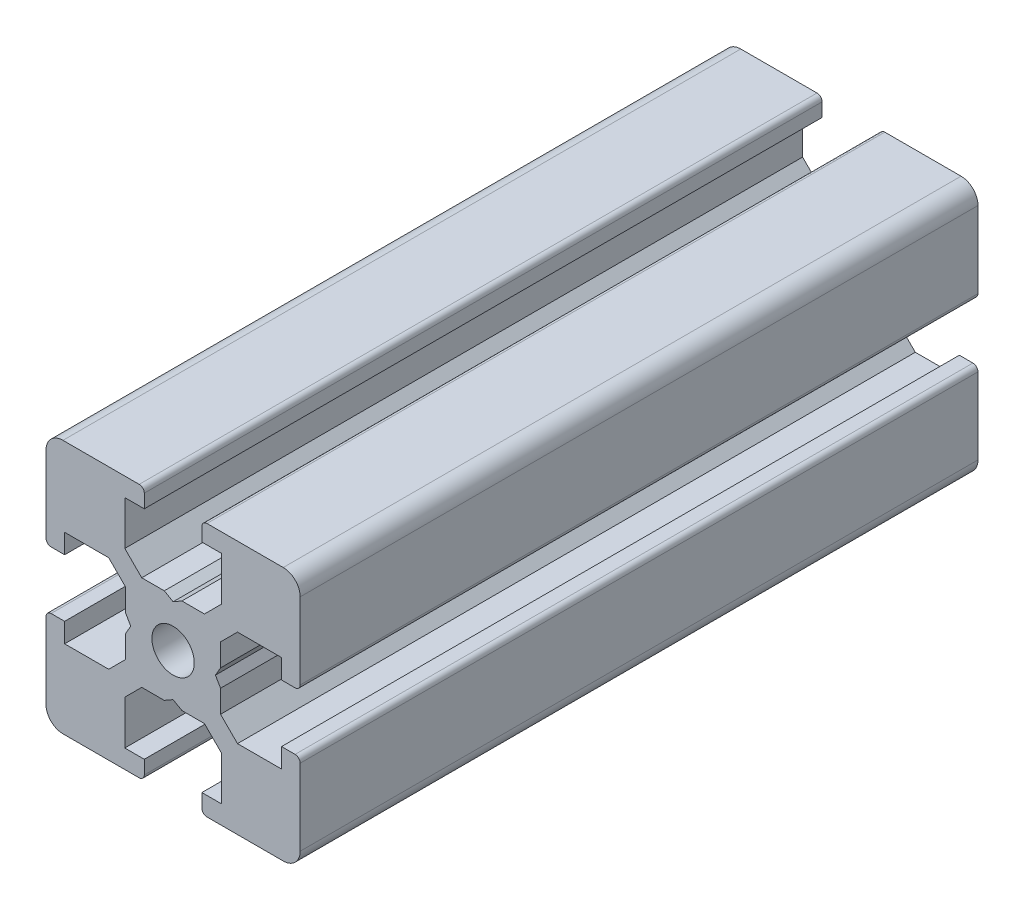
SolidWorks part; units mm, degrees
ref_plane "Front" through (0, 0, 0) normal (0, 0, 1) x (1, 0, 0)
ref_plane "Top" through (0, 0, 0) normal (0, 1, 0) x (1, 0, 0)
ref_plane "Right" through (0, 0, 0) normal (1, 0, 0) x (0, 0, -1)
ref_plane "Plane1" through (0, 0, 115) normal (0, 0, 1) x (1, 0, 0)
sketch "Sketch1" plane through (0, 0, 115) normal (0, 0, 1) x (1, 0, 0)
  line L0 (-7.5, 6.5) -> (-7.5, 2)
  line L1 (-7.2, 1.7) -> (-6.4, 1.7)
  line L2 (-6.4, 1.7) -> (-6.4, 2.85)
  line L3 (-6.4, 2.85) -> (-3.8, 2.85)
  line L4 (-3.8, 2.85) -> (-2.8, 1.85)
  line L5 (-2.8, 1.85) -> (-2.8, 0.5196)
  line L6 (-2.8, 0.5196) -> (-2.5, 0)
  line L7 (-2.5, 0) -> (-2.8, -0.5196)
  line L8 (-2.8, -0.5196) -> (-2.8, -1.85)
  line L9 (-2.8, -1.85) -> (-3.8, -2.85)
  line L10 (-3.8, -2.85) -> (-6.4, -2.85)
  line L11 (-6.4, -2.85) -> (-6.4, -1.7)
  line L12 (-6.4, -1.7) -> (-7.2, -1.7)
  line L13 (-7.5, -2) -> (-7.5, -6.5)
  line L14 (-6.5, -7.5) -> (-2, -7.5)
  line L15 (-1.7, -7.2) -> (-1.7, -6.4)
  line L16 (-1.7, -6.4) -> (-2.85, -6.4)
  line L17 (-2.85, -6.4) -> (-2.85, -3.8)
  line L18 (-2.85, -3.8) -> (-1.85, -2.8)
  line L19 (-1.85, -2.8) -> (-0.5196, -2.8)
  line L20 (-0.5196, -2.8) -> (0, -2.5)
  line L21 (0, -2.5) -> (0.5196, -2.8)
  line L22 (0.5196, -2.8) -> (1.85, -2.8)
  line L23 (1.85, -2.8) -> (2.85, -3.8)
  line L24 (2.85, -3.8) -> (2.85, -6.4)
  line L25 (2.85, -6.4) -> (1.7, -6.4)
  line L26 (1.7, -6.4) -> (1.7, -7.2)
  line L27 (2, -7.5) -> (6.5, -7.5)
  line L28 (7.5, -6.5) -> (7.5, -2)
  line L29 (7.2, -1.7) -> (6.4, -1.7)
  line L30 (6.4, -1.7) -> (6.4, -2.85)
  line L31 (6.4, -2.85) -> (3.8, -2.85)
  line L32 (3.8, -2.85) -> (2.8, -1.85)
  line L33 (2.8, -1.85) -> (2.8, -0.5196)
  line L34 (2.8, -0.5196) -> (2.5, 0)
  line L35 (2.5, 0) -> (2.8, 0.5196)
  line L36 (2.8, 0.5196) -> (2.8, 1.85)
  line L37 (2.8, 1.85) -> (3.8, 2.85)
  line L38 (3.8, 2.85) -> (6.4, 2.85)
  line L39 (6.4, 2.85) -> (6.4, 1.7)
  line L40 (6.4, 1.7) -> (7.2, 1.7)
  line L41 (7.5, 2) -> (7.5, 6.5)
  line L42 (6.5, 7.5) -> (2, 7.5)
  line L43 (1.7, 7.2) -> (1.7, 6.4)
  line L44 (1.7, 6.4) -> (2.85, 6.4)
  line L45 (2.85, 6.4) -> (2.85, 3.8)
  line L46 (2.85, 3.8) -> (1.85, 2.8)
  line L47 (1.85, 2.8) -> (0.5196, 2.8)
  line L48 (0.5196, 2.8) -> (0, 2.5)
  line L49 (0, 2.5) -> (-0.5196, 2.8)
  line L50 (-0.5196, 2.8) -> (-1.85, 2.8)
  line L51 (-1.85, 2.8) -> (-2.85, 3.8)
  line L52 (-2.85, 3.8) -> (-2.85, 6.4)
  line L53 (-2.85, 6.4) -> (-1.7, 6.4)
  line L54 (-1.7, 6.4) -> (-1.7, 7.2)
  line L55 (-2, 7.5) -> (-6.5, 7.5)
  circle A0 centre (0, 0) radius 1.25
  arc A1 (-7.5, 2) -> (-7.2, 1.7) centre (-7.2, 2) ccw
  arc A2 (-7.2, -1.7) -> (-7.5, -2) centre (-7.2, -2) ccw
  arc A3 (-7.5, -6.5) -> (-6.5, -7.5) centre (-6.5, -6.5) ccw
  arc A4 (-2, -7.5) -> (-1.7, -7.2) centre (-2, -7.2) ccw
  arc A5 (1.7, -7.2) -> (2, -7.5) centre (2, -7.2) ccw
  arc A6 (6.5, -7.5) -> (7.5, -6.5) centre (6.5, -6.5) ccw
  arc A7 (7.5, -2) -> (7.2, -1.7) centre (7.2, -2) ccw
  arc A8 (7.2, 1.7) -> (7.5, 2) centre (7.2, 2) ccw
  arc A9 (7.5, 6.5) -> (6.5, 7.5) centre (6.5, 6.5) ccw
  arc A10 (2, 7.5) -> (1.7, 7.2) centre (2, 7.2) ccw
  arc A11 (-1.7, 7.2) -> (-2, 7.5) centre (-2, 7.2) ccw
  arc A12 (-6.5, 7.5) -> (-7.5, 6.5) centre (-6.5, 6.5) ccw
extrude "Boss-Extrude1" add sketch "Sketch1" against normal blind 40
